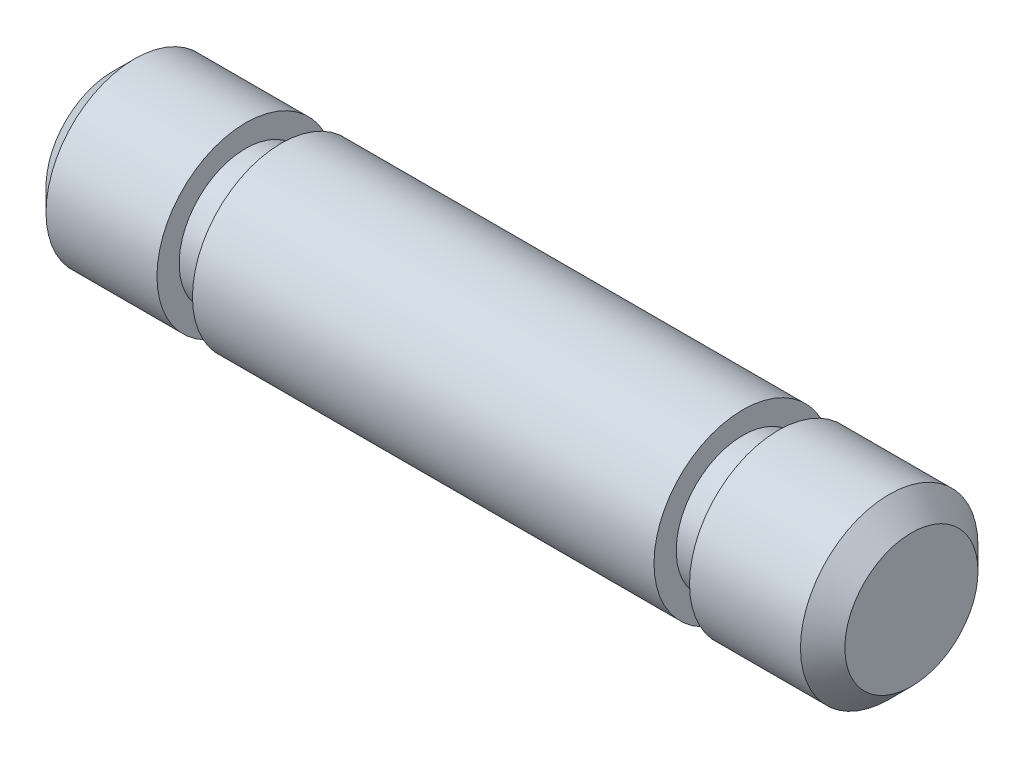
SolidWorks part; units mm, degrees
ref_plane "Front Plane" through (0, 0, 0) normal (0, 0, 1) x (1, 0, 0)
ref_plane "Top Plane" through (0, 0, 0) normal (0, 1, 0) x (1, 0, 0)
ref_plane "Right Plane" through (0, 0, 0) normal (1, 0, 0) x (0, 0, -1)
sketch "Sketch1" plane through (0, 0, 0) normal (1, 0, 0) x (0, 0, -1)
  circle A0 centre (0, 0) radius 2
  dimension "D1" = 4
extrude "Boss-Extrude1" add sketch "Sketch1" along normal mid plane 18
chamfer "Chamfer1" distance 0.5 angle 45 2 edges at (-9, 0, -2) (9, 0, -2)
sketch "Sketch2" plane through (9, 0, 0) normal (1, 0, 0) x (0, 0, -1)
  circle A0 centre (0, 0) radius 2
  circle A1 centre (0, 0) radius 1.5
  dimension "D1" = 3
extrude "Cut-Extrude1" cut sketch "Sketch2" against normal blind 0.8 from offset 3 offset against normal yes
mirror "Mirror1" about plane through (0, 0, 0) normal (1, 0, 0) of "Cut-Extrude1"
